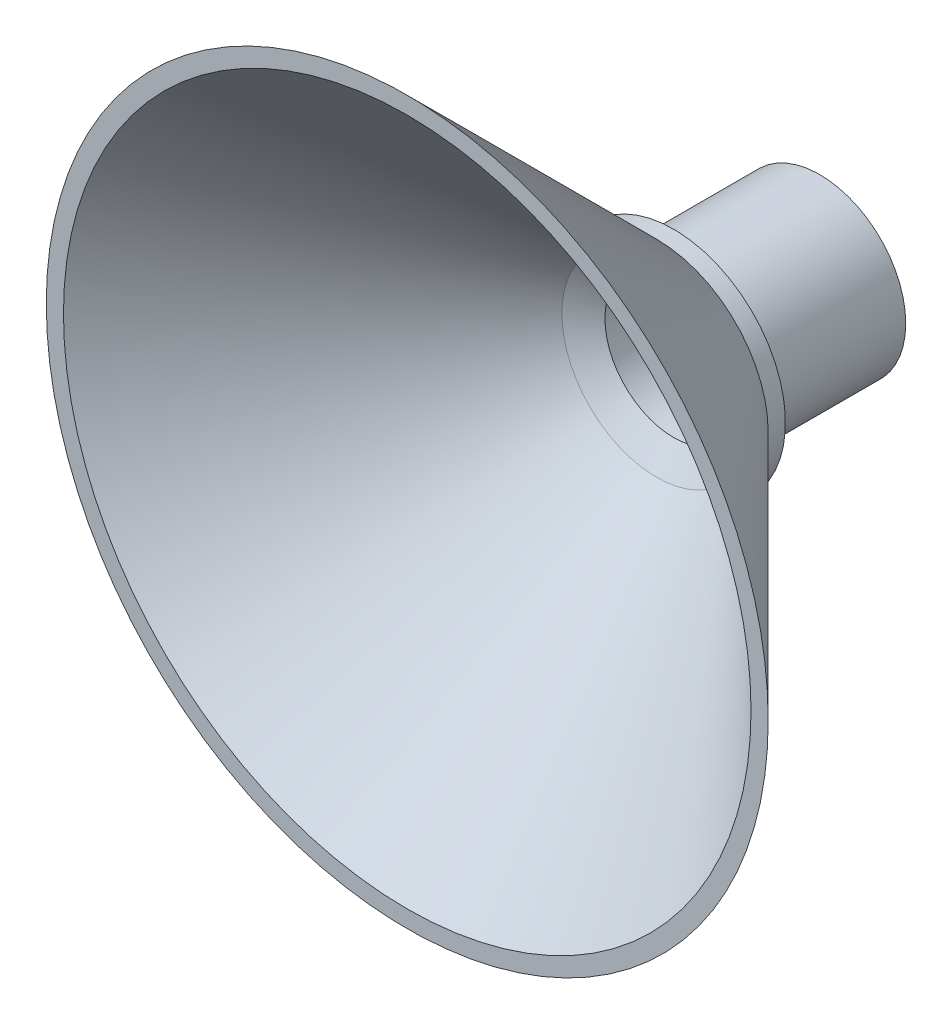
SolidWorks part; units mm, degrees
ref_plane "Front Plane" through (0, 0, 0) normal (0, 0, 1) x (1, 0, 0)
ref_plane "Top Plane" through (0, 0, 0) normal (0, 1, 0) x (1, 0, 0)
ref_plane "Right Plane" through (0, 0, 0) normal (1, 0, 0) x (0, 0, -1)
sketch "Sketch1" plane through (0, 0, 0) normal (0, 0, 1) x (1, 0, 0)
  circle A0 centre (0, 0) radius 10
  circle A1 centre (0, 0) radius 8
  dimension "D1" = 20
  dimension "D2" = 2
extrude "Boss-Extrude1" add sketch "Sketch1" along normal blind 17
sketch "Sketch3" plane through (0, 0, 0) normal (0, 1, 0) x (1, 0, 0)
  line L0 (-10, -17) -> (-13, -17)
  line L1 (-13, -17) -> (-13, -19)
  line L2 (-13, -19) -> (-11, -19)
  line L3 (-11, -19) -> (-8, -17)
  line L4 (-8, -17) -> (-10, -17)
  line L5 (0, 0) -> (0, -24.6318) construction
  dimension "D1" = 3
  dimension "D2" = 2
  dimension "D3" = 2
revolve "Revolve1" add sketch "Sketch3" angle 360 about L5
sketch "Sketch5" plane through (0, 0, 0) normal (0, 1, 0) x (1, 0, 0)
  line L0 (-13, -19) -> (-42, -48)
  line L1 (-42, -48) -> (-40, -48)
  line L2 (-40, -48) -> (-11, -19)
  line L3 (-11, -19) -> (-13, -19)
  line L4 (0, 0) -> (0, -51.5299) construction
  line L5 (8, 0) -> (-8, 0) construction
  line L6 (-13, -19) -> (13, -19) construction
  dimension "D1" = 40
  dimension "D2" = 135
revolve "Revolve2" add sketch "Sketch5" angle 360 about L4
